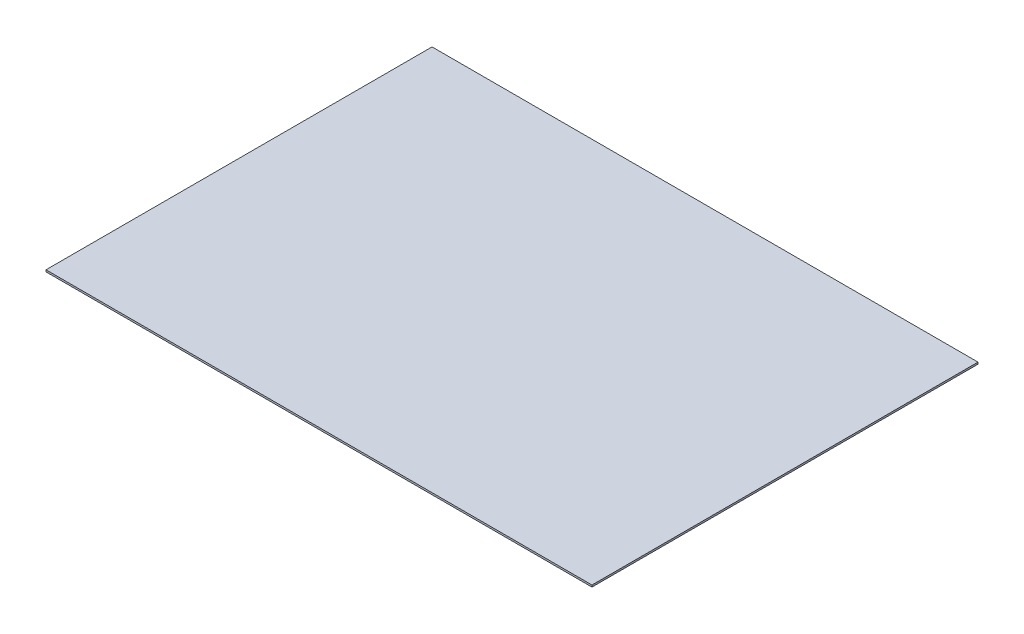
SolidWorks part; units mm, degrees
ref_plane "Front Plane" through (0, 0, 0) normal (0, 0, 1) x (1, 0, 0)
ref_plane "Top Plane" through (0, 0, 0) normal (0, 1, 0) x (1, 0, 0)
ref_plane "Right Plane" through (0, 0, 0) normal (1, 0, 0) x (0, 0, -1)
sketch "Sketch1" plane through (0, 0, 0) normal (0, 1, 0) x (1, 0, 0)
  line L1 (0, 0) -> (297, 0)
  line L2 (0, 0) -> (0, 210)
  line L3 (0, 210) -> (297, 210)
  line L4 (297, 0) -> (297, 210)
  dimension "D1" = 210
  dimension "D2" = 297
extrude "Boss-Extrude1" add sketch "Sketch1" along normal blind 1
